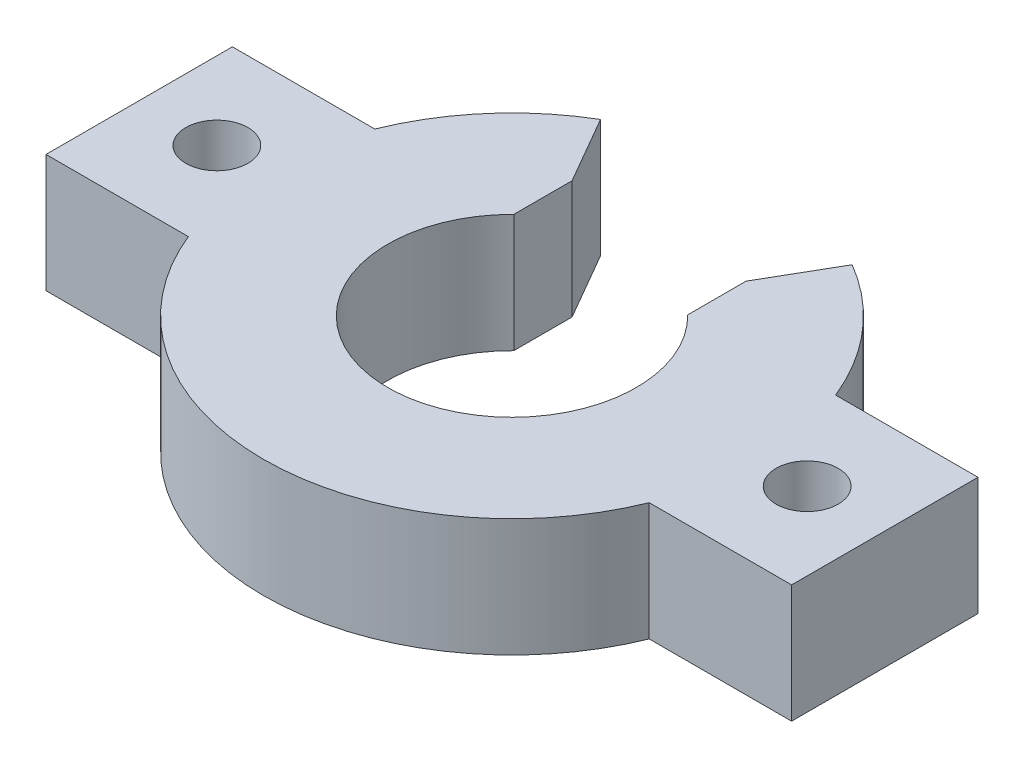
SolidWorks part; units mm, degrees
ref_plane "前视基准面" through (0, 0, 0) normal (0, 0, 1) x (1, 0, 0)
ref_plane "上视基准面" through (0, 0, 0) normal (0, 1, 0) x (1, 0, 0)
ref_plane "右视基准面" through (0, 0, 0) normal (1, 0, 0) x (0, 0, -1)
sketch "草图1" plane through (0, 0, 0) normal (0, 1, 0) x (1, 0, 0)
  circle A0 centre (0, 0) radius 4
  circle A1 centre (0, 0) radius 8
  dimension "D1" = 8
  dimension "D2" = 4
extrude "凸台-拉伸1" add sketch "草图1" along normal blind 3.8
sketch "草图4" plane through (0, 3.8, 0) normal (0, 1, 0) x (1, 0, 0)
  line L0 (0, 0) -> (-6, 0) construction
  line L9 (0, 9.0316) -> (0, -8.9214) construction
  line L12 (-12, 3) -> (-6, 3)
  line L13 (-12, 3) -> (-12, -3)
  line L14 (-12, -3) -> (-6, -3)
  line L15 (-6, 3) -> (-6, -3)
  line L16 (12, -3) -> (6, -3)
  line L17 (6, 3) -> (6, -3)
  line L18 (12, 3) -> (6, 3)
  line L19 (12, 3) -> (12, -3)
  circle A1 centre (0, 0) radius 8 construction
  dimension "D1" = 6
  dimension "D2" = 6
  dimension "D3" = 6
extrude "凸台-拉伸2" add sketch "草图4" against normal up to surface (3.8 mm away) up to face at (0, 0, 8)
sketch "草图5" plane through (0, 0, 0) normal (0, -1, 0) x (1, 0, 0)
  line L0 (-12, -3) -> (-12, 3) construction
  line L2 (-12, 3) -> (-7.4162, 3) construction
  line L3 (0, 9.1374) -> (0, -9.5753) construction
  circle A0 centre (-9.5, 0) radius 2
  circle A1 centre (9.5, 0) radius 2
  dimension "D1" = 4
  dimension "D2" = 2.5
  dimension "D3" = 3
extrude "切除-拉伸3" cut sketch "草图5" against normal blind 1
sketch "草图6" plane through (0, 1, 0) normal (0, -1, 0) x (1, 0, 0)
  line L0 (0, 9.8368) -> (0, -11.0559) construction
  circle A0 centre (-9.5, 0) radius 1
  circle A1 centre (9.5, 0) radius 1
  dimension "D1" = 2
extrude "切除-拉伸4" cut sketch "草图6" against normal through all
sketch "草图7" plane through (0, 3.8, 0) normal (0, 1, 0) x (1, 0, 0)
  line L4 (-4.05, 6.8991) -> (-2.8, 4.734)
  line L5 (-2.8, 4.734) -> (-2.8, 2.8566)
  line L6 (0, 10.1867) -> (0, -10.304) construction
  line L7 (2.8, 4.734) -> (2.8, 2.8566)
  line L8 (4.05, 6.8991) -> (2.8, 4.734)
  arc A1 (7.4162, 3) -> (-7.4162, 3) centre (0, 0) ccw construction
  circle A2 centre (0, 0) radius 4 construction
  arc A3 (2.8, 2.8566) -> (-2.8, 2.8566) centre (0, 0) ccw
  arc A4 (4.05, 6.8991) -> (-4.05, 6.8991) centre (0, 0) ccw
  dimension "D1" = 2.8
  dimension "D2" = 150
  dimension "D3" = 2.5
extrude "切除-拉伸5" cut sketch "草图7" against normal through all
